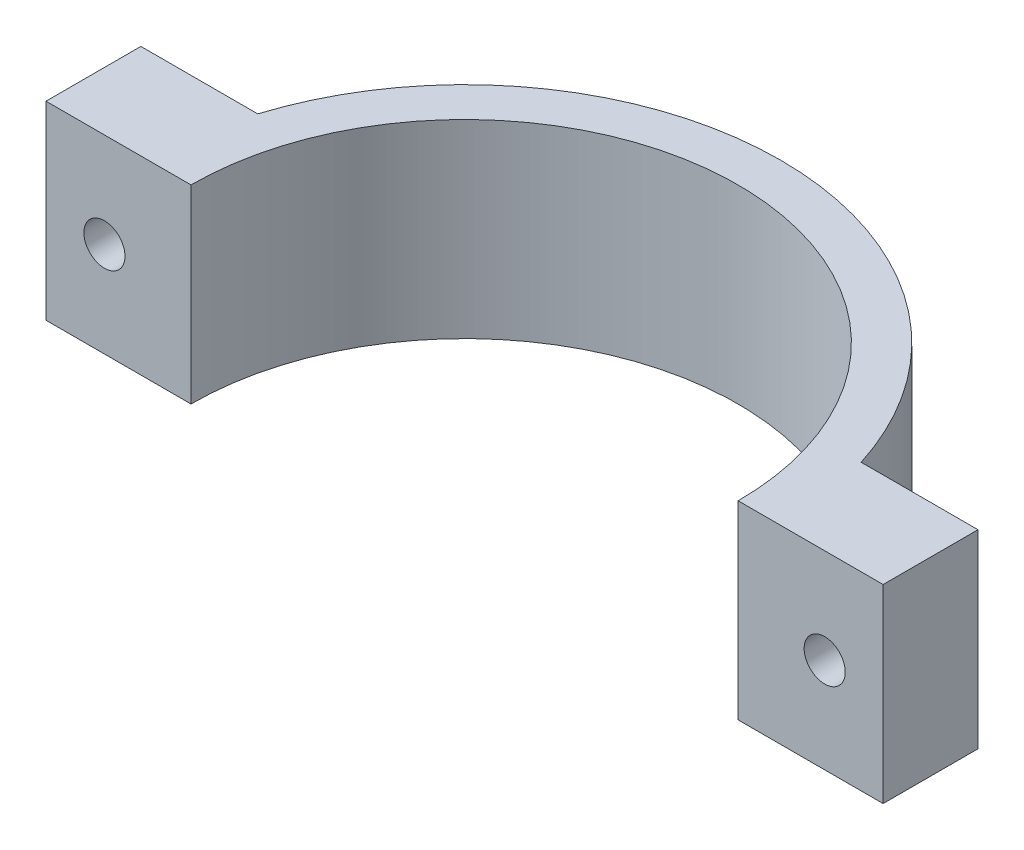
SolidWorks part; units mm, degrees
ref_plane "Front Plane" through (0, 0, 0) normal (0, 0, 1) x (1, 0, 0)
ref_plane "Top Plane" through (0, 0, 0) normal (0, 1, 0) x (1, 0, 0)
ref_plane "Right Plane" through (0, 0, 0) normal (1, 0, 0) x (0, 0, -1)
sketch "Sketch1" plane through (0, 0, 0) normal (0, 1, 0) x (1, 0, 0)
  line L3 (0, 0) -> (0, 43.25) construction
  line L14 (-66.175, 0) -> (-66.175, 15)
  line L16 (43.25, 0) -> (66.175, 0)
  line L17 (66.175, 0) -> (66.175, 15)
  line L18 (-66.175, 0) -> (-43.25, 0)
  line L19 (-66.175, 15) -> (-47.697, 15)
  line L20 (47.697, 15) -> (66.175, 15)
  circle A0 centre (0, 0) radius 43.25 construction
  arc A1 (-43.25, 0) -> (43.25, 0) centre (0, 0) cw
  arc A2 (-47.697, 15) -> (47.697, 15) centre (0, 0) cw
  dimension "D1" = 86.5
  dimension "D2" = 50
  dimension "D3" = 15
  dimension "D4" = 132.35
extrude "Boss-Extrude1" add sketch "Sketch1" along normal mid plane 30
sketch "Sketch2" plane through (0, 0, -15) normal (0, 0, -1) x (-1, 0, 0)
  line L0 (56.936, -15) -> (56.936, 15) construction
  line L1 (47.697, -15) -> (66.175, -15) construction
  line L2 (47.697, 15) -> (66.175, 15) construction
  line L3 (0, 0) -> (0, 15) construction
  line L4 (47.697, 15) -> (-47.697, 15) construction
  circle A1 centre (56.936, 0) radius 3.25
  circle A2 centre (-56.936, 0) radius 3.25
  dimension "D1" = 6.5
extrude "Cut-Extrude1" cut sketch "Sketch2" against normal through all
